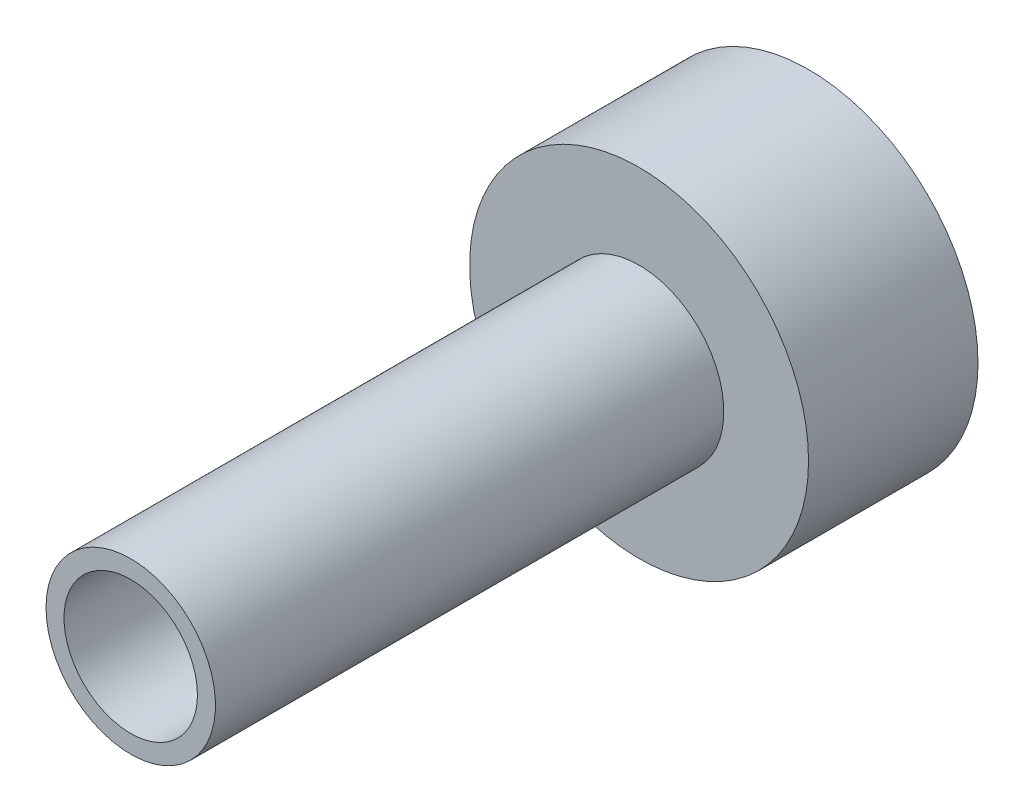
SolidWorks part; units mm, degrees
ref_plane "Front Plane" through (0, 0, 0) normal (0, 0, 1) x (1, 0, 0)
ref_plane "Top Plane" through (0, 0, 0) normal (0, 1, 0) x (1, 0, 0)
ref_plane "Right Plane" through (0, 0, 0) normal (1, 0, 0) x (0, 0, -1)
sketch "Sketch1" plane through (0, 0, 0) normal (0, 0, 1) x (1, 0, 0)
  circle A0 centre (0, 0) radius 2.5
  circle A1 centre (0, 0) radius 6.35
  dimension "D1" = 5
  dimension "D2" = 12.7
extrude "Boss-Extrude1" add sketch "Sketch1" along normal blind 6.35
sketch "Sketch2" plane through (0, 0, 6.35) normal (0, 0, 1) x (1, 0, 0)
  circle A0 centre (0, 0) radius 2.5
  circle A1 centre (0, 0) radius 3.175
  dimension "D1" = 6.35
extrude "Boss-Extrude2" add sketch "Sketch2" along normal blind 19.05
ref_plane "Plane1" through (-6.35, 0, 0) normal (-1, 0, 0) x (0, 0, 1)
hole_wizard "#4-40 Tapped Hole1" positions "Sketch5" profile "Sketch4" tap size "#4-40" standard "Ansi Inch"
sketch "Sketch5" plane through (-6.35, 0, 0) normal (-1, 0, 0) x (0, 0, 1)
  line L6 (3.1916, 7.2836) -> (3.1916, -10.958) construction
  line L9 (7.193, 0) -> (-1.2805, 0) construction
  point P1 (3.1916, 0)
sketch "Sketch4" plane through (-6.35, 0, 3.1916) normal (0, 1, 0) x (0, 0, 1)
  line L0 (0, 0) -> (0, 7.0282)
  line L1 (0, 7.0282) -> (1.1303, 6.349)
  line L2 (1.1303, 6.349) -> (1.1303, 0)
  line L5 (1.1303, 0) -> (0, 0)
  line L10 (0, 7.0282) -> (-1.1303, 6.349) construction
  line L11 (0, -6.35) -> (0, 107.95) construction
  dimension "Tap Drill Dia." = 2.2606
  dimension "Tap Drill Depth" = 6.349
  dimension "Drill Angle" = 118
